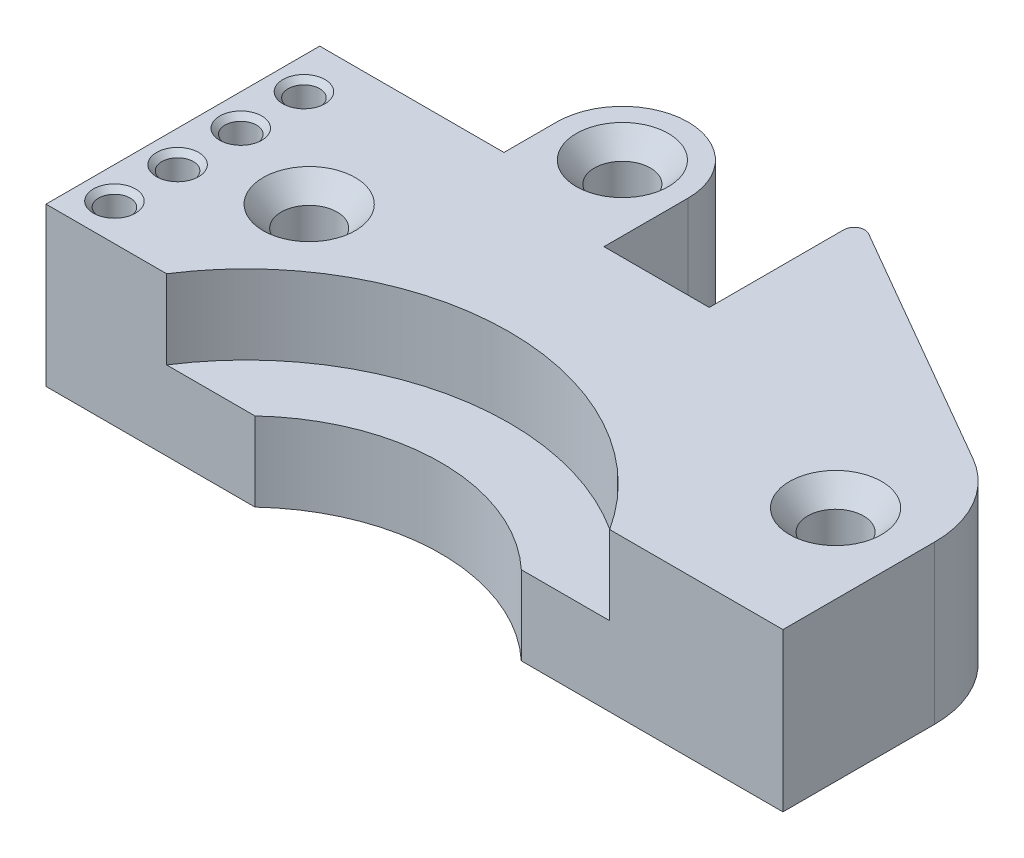
SolidWorks part; units mm, degrees
material "AISI 304"
ref_plane "Front Plane" through (0, 0, 0) normal (0, 0, 1) x (1, 0, 0)
ref_plane "Top Plane" through (0, 0, 0) normal (0, 1, 0) x (1, 0, 0)
ref_plane "Right Plane" through (0, 0, 0) normal (1, 0, 0) x (0, 0, -1)
sketch "Sketch1" plane through (0, 0, 0) normal (0, 1, 0) x (1, 0, 0)
  line L0 (0, 0) -> (50.4213, 0)
  line L1 (177.8, 0) -> (177.8, 36.5912)
  line L2 (165.1, 58.5883) -> (101.6, 95.25)
  line L3 (101.6, 95.25) -> (101.6, 58.42)
  line L4 (101.6, 58.42) -> (76.2, 58.42)
  line L5 (76.2, 58.42) -> (76.2, 78.74)
  line L6 (44.45, 78.74) -> (44.45, 66.04)
  line L7 (44.45, 66.04) -> (0, 66.04)
  line L8 (0, 66.04) -> (0, 0)
  line L10 (114.6787, 0) -> (177.8, 0)
  arc A0 (50.4213, 0) -> (114.6787, 0) centre (82.55, -34.29) cw
  arc A1 (177.8, 36.5912) -> (165.1, 58.5883) centre (152.4, 36.5912) ccw
  arc A2 (76.2, 78.74) -> (44.45, 78.74) centre (60.325, 78.74) ccw
  dimension "D3" = 25.4
  dimension "D8" = 46.99
  dimension "D9" = 82.55
  dimension "D11" = 15.875
  dimension "D1" = 177.8
  dimension "D2" = 60
  dimension "D4" = 25.4
  dimension "D5" = 66.04
  dimension "D6" = 95.25
  dimension "D7" = 58.42
  dimension "D10" = 34.29
  dimension "D12" = 44.45
  dimension "D13" = 12.7
extrude "Boss-Extrude1" add sketch "Sketch1" along normal mid plane 38.1
hole_wizard "1/4-20 Tapped Hole1" positions "Sketch3" profile "Sketch2" tap size "1/4-20" standard "ANSI Inch"
sketch "Sketch3" plane through (66.6445, 0, -115.4316) normal (0.5, 0, -0.866) x (-0.866, 0, -0.5)
  line L0 (0, 0) -> (-66.04, 0) construction
  point P0 (-66.04, 0)
  dimension "D1" = 66.04
sketch "Sketch2" plane through (123.8368, 0, -82.4116) normal (0, 1, 0) x (-0.866, 0, -0.5)
  line L0 (0, 0) -> (0, 20.5838)
  line L1 (0, 20.5838) -> (2.5527, 19.05)
  line L2 (2.5527, 19.05) -> (2.5527, 0)
  line L5 (2.5527, 0) -> (0, 0)
  line L10 (0, 20.5838) -> (-2.5527, 19.05) construction
  line L11 (0, -6.35) -> (0, 107.95) construction
  dimension "Tap Drill Dia." = 5.1054
  dimension "Tap Drill Depth" = 19.05
  dimension "Drill Angle" = 118
cosmetic thread "Hole Thread1" parameters "D1"=12.7, "D2"=6.35
sketch "Sketch4" plane through (0, 19.05, 0) normal (0, 1, 0) x (1, 0, 0)
  circle A0 centre (82.55, -34.29) radius 63.5
  dimension "D1" = 127
extrude "Cut-Extrude1" cut sketch "Sketch4" against normal blind 19.05
hole_wizard "CSK for 1/2 Flat Head Machine Screw1" positions "Sketch6" profile "Sketch5" countersink size "1/2" standard "ANSI Inch" end condition through all
sketch "Sketch6" plane through (0, 19.05, 0) normal (0, 1, 0) x (1, 0, 0)
  line L0 (0, 66.04) -> (0, 0) construction
  line L1 (177.8, 0) -> (177.8, 36.5912) construction
  line L2 (31.75, 31.75) -> (158.75, 31.75) construction
  line L4 (0, 0) -> (29.1043, 0) construction
  point P0 (60.325, 78.74)
  point P3 (31.75, 31.75)
  point P5 (158.75, 31.75)
  dimension "D1" = 31.75
  dimension "D2" = 19.05
  dimension "D3" = 31.75
sketch "Sketch5" plane through (60.325, 19.05, -78.74) normal (1, 0, 0) x (0, 0, 1)
  line L0 (0, 0) -> (0, 38.1)
  line L1 (0, 38.1) -> (6.7462, 38.1)
  line L2 (6.7462, 38.1) -> (6.7462, 5.0228)
  line L3 (6.7462, 5.0228) -> (11.1125, 0)
  line L5 (11.1125, 0) -> (0, 0)
  line L6 (-6.7462, 5.0228) -> (-11.1125, 0) construction
  line L11 (0, -6.35) -> (0, 107.95) construction
  dimension "Thru Hole Dia." = 13.4925
  dimension "Thru Hole Depth" = 38.1
  dimension "Near C'Sink Dia." = 22.225
  dimension "Near C'Sink Angle" = 82
fillet "Fillet1" radius 2.54 1 edges at (101.6, 0, -95.25)
ref_plane "Plane1" through (7.62, 0, 0) normal (1, 0, 0) x (0, 0, -1)
sketch "Sketch8" plane through (7.62, 0, 0) normal (1, 0, 0) x (0, 0, -1)
  line L0 (3.81, 19.05) -> (5.08, 17.78)
  line L1 (66.04, 19.05) -> (0, 19.05) construction
  line L2 (5.08, 17.78) -> (5.08, 10.16)
  line L3 (5.08, 10.16) -> (6.604, 9.2801)
  line L4 (6.604, 9.2801) -> (6.604, 2.6436)
  line L5 (6.604, 2.6436) -> (8.89, 1.27)
  line L6 (8.89, 1.27) -> (8.89, 19.05)
  line L7 (8.89, 19.05) -> (3.81, 19.05)
  line L8 (0, 19.05) -> (0, -19.05) construction
  dimension "D1" = 45
  dimension "D2" = 60
  dimension "D3" = 59
  dimension "D4" = 3.81
  dimension "D5" = 8.89
  dimension "D6" = 5.08
  dimension "D7" = 8.89
  dimension "D8" = 2.286
  dimension "D9" = 17.78
revolve "Cut-Revolve1" cut sketch "Sketch8" angle 360 about L6
pattern_linear "LPattern1" count 4 spacing 15.24 along (0, 0, -1) of "Cut-Revolve1"
hole_wizard "1/16 NPT Tapped Hole1" positions "Sketch10" profile "Sketch9" size "1/16" standard "ANSI Inch"
sketch "Sketch10" plane through (0, 0, -66.04) normal (0, 0, -1) x (-1, 0, 0)
  line L0 (0, 19.05) -> (0, -19.05) construction
  point P0 (-7.62, 2.54)
  dimension "D1" = 7.62
  dimension "D2" = 16.51
sketch "Sketch9" plane through (7.62, 2.54, -66.04) normal (1, 0, 0) x (0, 1, 0)
  line L0 (0, 0) -> (0, 63.5687)
  line L1 (3.0734, 61.722) -> (0, 63.5687)
  line L2 (-3.0734, 61.722) -> (0, 63.5687) construction
  line L3 (3.0734, 61.722) -> (3.0734, 6.858)
  line L4 (3.0734, 6.858) -> (3.7769, 6.858)
  line L5 (3.7769, 6.858) -> (3.9679, 0.4771)
  line L6 (3.9679, 0.4771) -> (4.445, 0)
  line L7 (4.445, 0) -> (0, 0)
  line L8 (0, -6.35) -> (0, 107.95) construction
  line L9 (-3.9679, 0.4771) -> (-4.445, 0) construction
  line L11 (-3.0734, 6.858) -> (-3.7769, 6.858) construction
  line L12 (-3.7769, 6.858) -> (-3.9679, 0.4771) construction
  dimension "Tap Drill Dia." = 6.1468
  dimension "Tap Drill Depth" = 61.722
  dimension "Thread Dia." = 7.9358
  dimension "Thread Angle" = 3.43
  dimension "Thread Depth" = 6.858
  dimension "C'Sink Dia." = 8.89
  dimension "C'Sink Angle" = 90
  dimension "Drill Angle" = 118
